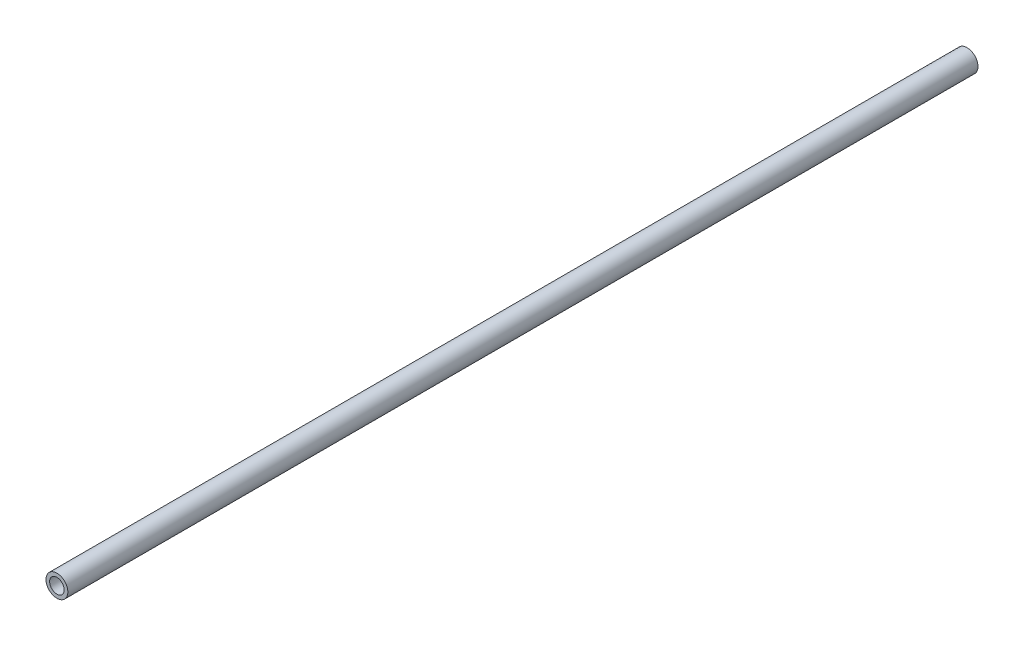
SolidWorks part; units mm, degrees
material "Thornel Mat VMA"
ref_plane "Front Plane" through (0, 0, 0) normal (0, 0, 1) x (1, 0, 0)
ref_plane "Top Plane" through (0, 0, 0) normal (0, 1, 0) x (1, 0, 0)
ref_plane "Right Plane" through (0, 0, 0) normal (1, 0, 0) x (0, 0, -1)
sketch "Sketch1" plane through (0, 0, 0) normal (0, 0, 1) x (1, 0, 0)
  circle A0 centre (0, 0) radius 2
  circle A1 centre (0, 0) radius 3
  dimension "D1" = 4
  dimension "D2" = 6
extrude "Boss-Extrude1" add sketch "Sketch1" along normal blind 250
